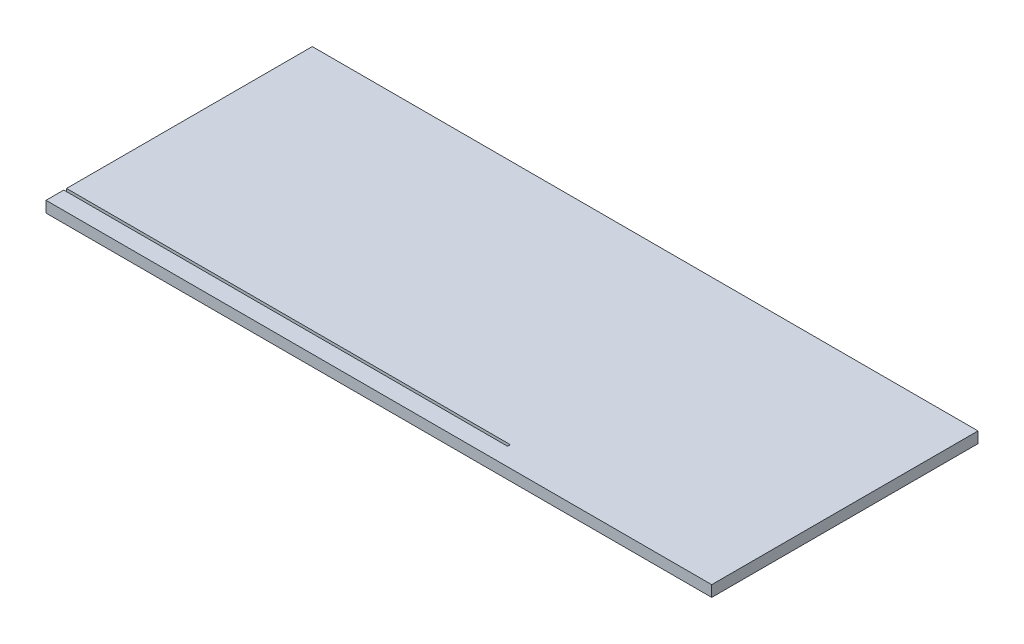
SolidWorks part; units mm, degrees
ref_plane "Front Plane" through (0, 0, 0) normal (0, 0, 1) x (1, 0, 0)
ref_plane "Top Plane" through (0, 0, 0) normal (0, 1, 0) x (1, 0, 0)
ref_plane "Right Plane" through (0, 0, 0) normal (1, 0, 0) x (0, 0, -1)
sketch "Sketch1" plane through (0, 0, 0) normal (0, 1, 0) x (1, 0, 0)
  line L1 (0, 0) -> (600, 0)
  line L2 (0, 0) -> (0, 240)
  line L3 (0, 240) -> (600, 240)
  line L4 (600, 0) -> (600, 240)
  dimension "D1" = 600
  dimension "D2" = 240
extrude "Boss-Extrude1" add sketch "Sketch1" along normal blind 10
sketch "Sketch2" plane through (0, 10, 0) normal (0, 1, 0) x (1, 0, 0)
  line L0 (0, 240) -> (0, 0) construction
  line L1 (400, 16) -> (0, 16)
  line L2 (400, 16) -> (400, 18.5)
  line L3 (400, 18.5) -> (0, 18.5)
  line L4 (0, 16) -> (0, 18.5)
  line L5 (0, 0) -> (600, 0) construction
  dimension "D1" = 16
  dimension "D2" = 2.5
  dimension "D3" = 400
extrude "Cut-Extrude1" cut sketch "Sketch2" against normal blind 2.5
